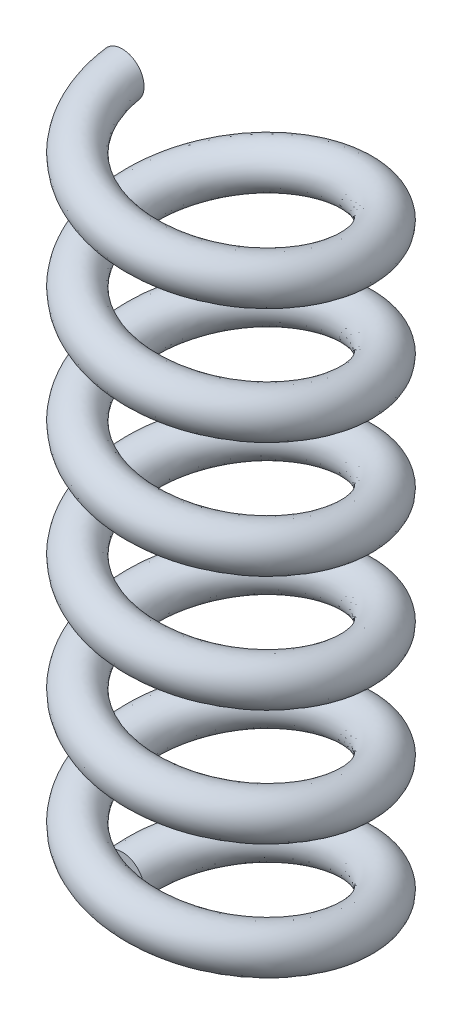
SolidWorks part; units mm, degrees
ref_plane "Front Plane" through (0, 0, 0) normal (0, 0, 1) x (1, 0, 0)
ref_plane "Top Plane" through (0, 0, 0) normal (0, 1, 0) x (1, 0, 0)
ref_plane "Right Plane" through (0, 0, 0) normal (1, 0, 0) x (0, 0, -1)
sketch "Sketch1" plane through (0, 0, 0) normal (0, 1, 0) x (1, 0, 0)
  circle A0 centre (0, 0) radius 3.125
  dimension "D1" = 6.25
curve "Helix/Spiral1"
sketch "Sketch2" plane through (0, 0, 0) normal (0, 0, 1) x (1, 0, 0)
  circle A0 centre (-3.125, 0) radius 0.625
  spline S0 degree 3 poles (-3.125, 0) (-3.125, 0.069) (-2.9623, 0.2085) (-2.2672, 0.4166) (-1.227, 0.625) (0, 0.8333) (1.227, 1.0417) (2.2672, 1.25) (2.9623, 1.4583) (3.2064, 1.6667) (2.9623, 1.875) (2.2672, 2.0833) (1.227, 2.2917) (0, 2.5) (-1.227, 2.7083) (-2.2672, 2.9167) (-2.9623, 3.125) (-3.2064, 3.3333) (-2.9623, 3.5417) (-2.2672, 3.75) (-1.227, 3.9583) (0, 4.1667) (1.227, 4.375) (2.2672, 4.5833) (2.9623, 4.7917) (3.2064, 5) (2.9623, 5.2083) (2.2672, 5.4167) (1.227, 5.625) (0, 5.8333) (-1.227, 6.0417) (-2.2672, 6.25) (-2.9623, 6.4583) (-3.2064, 6.6667) (-2.9623, 6.875) (-2.2672, 7.0833) (-1.227, 7.2917) (0, 7.5) (1.227, 7.7083) (2.2672, 7.9167) (2.9623, 8.125) (3.2064, 8.3333) (2.9623, 8.5417) (2.2672, 8.75) (1.227, 8.9583) (0, 9.1667) (-1.227, 9.375) (-2.2672, 9.5833) (-2.9623, 9.7917) (-3.2064, 10) (-2.9623, 10.2083) (-2.2672, 10.4167) (-1.227, 10.625) (0, 10.8333) (1.227, 11.0417) (2.2672, 11.25) (2.9623, 11.4583) (3.2064, 11.6667) (2.9623, 11.875) (2.2672, 12.0833) (1.227, 12.2917) (0, 12.5) (-1.227, 12.7083) (-2.2672, 12.9167) (-2.9623, 13.125) (-3.2064, 13.3333) (-2.9623, 13.5417) (-2.2672, 13.75) (-1.227, 13.9583) (0, 14.1667) (1.227, 14.375) (2.2672, 14.5833) (2.9623, 14.7917) (3.2064, 15) (2.9623, 15.2083) (2.2672, 15.4167) (1.227, 15.625) (0, 15.8333) (-1.227, 16.0417) (-2.2672, 16.25) (-2.9623, 16.4583) (-3.2064, 16.6667) (-2.9623, 16.875) (-2.2672, 17.0833) (-1.227, 17.2917) (0, 17.5) (1.227, 17.7083) (2.2672, 17.9167) (2.9623, 18.125) (3.2064, 18.3333) (2.9623, 18.5417) (2.2672, 18.75) (1.227, 18.9583) (0, 19.1667) (-1.227, 19.375) (-2.2672, 19.5834) (-2.9623, 19.7915) (-3.125, 19.931) (-3.125, 20) knots 0 0 0 0 0.010417 0.020833 0.03125 0.041667 0.052083 0.0625 0.072917 0.083333 0.09375 0.104167 0.114583 0.125 0.135417 0.145833 0.15625 0.166667 0.177083 0.1875 0.197917 0.208333 0.21875 0.229167 0.239583 0.25 0.260417 0.270833 0.28125 0.291667 0.302083 0.3125 0.322917 0.333333 0.34375 0.354167 0.364583 0.375 0.385417 0.395833 0.40625 0.416667 0.427083 0.4375 0.447917 0.458333 0.46875 0.479167 0.489583 0.5 0.510417 0.520833 0.53125 0.541667 0.552083 0.5625 0.572917 0.583333 0.59375 0.604167 0.614583 0.625 0.635417 0.645833 0.65625 0.666667 0.677083 0.6875 0.697917 0.708333 0.71875 0.729167 0.739583 0.75 0.760417 0.770833 0.78125 0.791667 0.802083 0.8125 0.822917 0.833333 0.84375 0.854167 0.864583 0.875 0.885417 0.895833 0.90625 0.916667 0.927083 0.9375 0.947917 0.958333 0.96875 0.979167 0.989583 1 1 1 1 construction
  dimension "D1" = 1.25
sweep "Sweep1" add profiles "Sketch2" path "Helix/Spiral1"
ref_plane "Plane1" through (0, 20, 0) normal (0, 1, 0) x (1, 0, 0)
